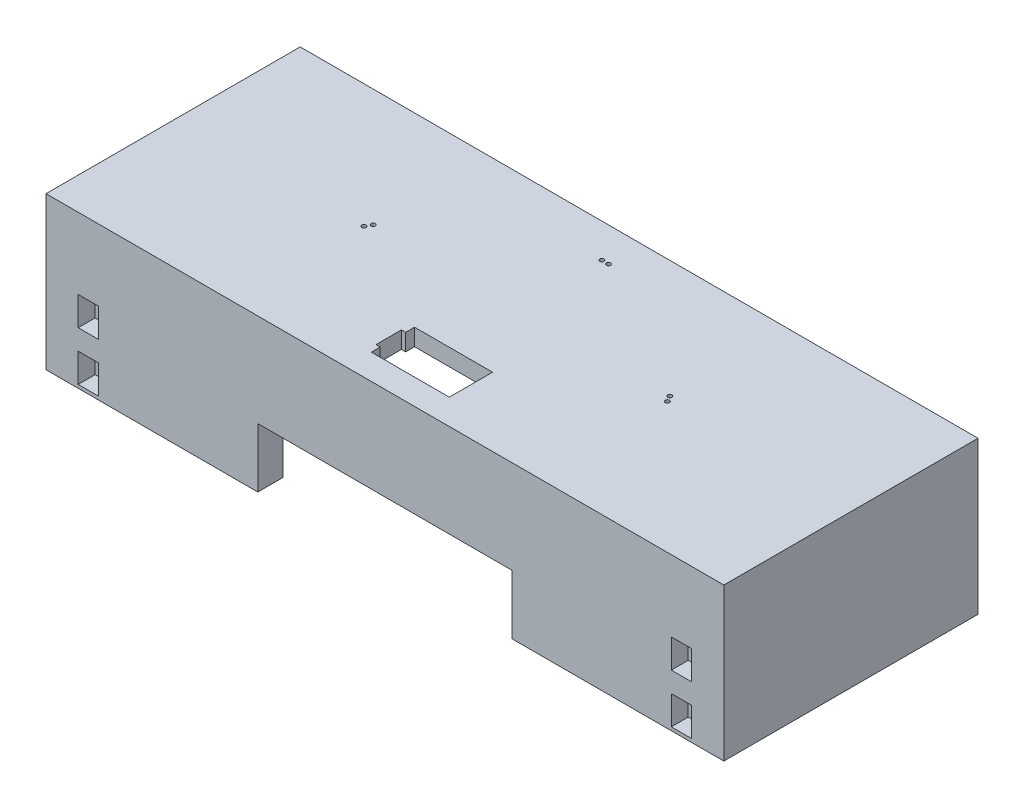
SolidWorks part; units mm, degrees
ref_plane "Front Plane" through (0, 0, 0) normal (0, 0, 1) x (1, 0, 0)
ref_plane "Top Plane" through (0, 0, 0) normal (0, 1, 0) x (1, 0, 0)
ref_plane "Right Plane" through (0, 0, 0) normal (1, 0, 0) x (0, 0, -1)
sketch "Sketch1" plane through (0, 0, 0) normal (0, 1, 0) x (1, 0, 0)
  line L1 (100, 37.5) -> (-100, 37.5)
  line L2 (100, 37.5) -> (100, -37.5)
  line L3 (100, -37.5) -> (-100, -37.5)
  line L4 (-100, 37.5) -> (-100, -37.5)
  line L5 (100, 37.5) -> (-100, -37.5) construction
  line L6 (100, -37.5) -> (-100, 37.5) construction
  point P0 (0, 0)
  dimension "D1" = 200
  dimension "D2" = 75
extrude "Boss-Extrude1" add sketch "Sketch1" along normal mid plane 45
shell "Shell1" thickness 5
sketch "Sketch2" plane through (0, 22.5, 0) normal (0, 1, 0) x (1, 0, 0)
  line L0 (-100, -37.5) -> (100, -37.5) construction
  line L1 (11.5, -30) -> (-11.5, -30)
  line L2 (11.5, -30) -> (11.5, -17.25)
  line L3 (11.5, -17.25) -> (-11.5, -17.25)
  line L4 (-11.5, -30) -> (-11.5, -17.25)
  line L5 (11.5, -30) -> (-11.5, -17.25) construction
  line L6 (11.5, -17.25) -> (-11.5, -30) construction
  point P0 (0, -23.625)
  dimension "D1" = 23
  dimension "D2" = 12.75
  dimension "D3" = 7.5
extrude "Cut-Extrude1" cut sketch "Sketch2" against normal through all
sketch "Sketch3" plane through (0, 22.5, 0) normal (0, 1, 0) x (1, 0, 0)
  line L0 (-11.5, -23.625) -> (11.5, -23.625) construction
  line L1 (-11.5, -17.25) -> (-11.5, -30) construction
  line L2 (11.5, -30) -> (11.5, -17.25) construction
  line L3 (0, -1036.125) -> (0, 48963.875) construction
  line L4 (100, 37.5) -> (-100, 37.5) construction
  line L5 (-44.2755, 1.9375) -> (0, -23.625) construction
  circle A0 centre (0, -23.625) radius 51.125 construction
  point P6 (0, -23.625)
  point P8 (0, 27.5)
  point P14 (-44.2755, 1.9375)
  point P16 (44.2755, 1.9375)
  dimension "D1" = 10
  dimension "D2" = 60
sketch "Sketch4" plane through (0, 0, 32.5) normal (0, 0, -1) x (-1, 0, 0)
  line L4 (-95, -22.5) -> (95, -22.5)
  line L5 (95, -22.5) -> (95, 17.5)
  line L6 (95, 17.5) -> (-95, 17.5)
  line L7 (-95, 17.5) -> (-95, -22.5)
  line L8 (-95, -22.5) -> (95, -22.5)
  line L9 (95, -22.5) -> (95, 17.5)
  line L10 (95, 17.5) -> (-95, 17.5)
  line L11 (-95, 17.5) -> (-95, -22.5)
  dimension "D1" = 0
extrude "Boss-Extrude2" add sketch "Sketch4" along normal blind 2.5
sketch "Sketch5" plane through (0, 0, 37.5) normal (0, 0, 1) x (1, 0, 0)
  line L0 (-90, -6.5) -> (-90, 1) construction
  line L1 (-90, 1) -> (-85, 1) construction
  line L2 (-85, 1) -> (-85, -6.5) construction
  line L3 (-85, -6.5) -> (-90, -6.5) construction
  line L4 (-85, -21) -> (-90, -21) construction
  line L5 (-90, -21) -> (-90, -13.5) construction
  line L6 (-90, -13.5) -> (-85, -13.5) construction
  line L7 (-85, -13.5) -> (-85, -21) construction
  line L8 (90, -13.5) -> (90, -21) construction
  line L9 (90, -21) -> (85, -21) construction
  line L10 (85, -21) -> (85, -13.5) construction
  line L11 (85, -13.5) -> (90, -13.5) construction
  line L12 (90, 1) -> (90, -6.5) construction
  line L13 (90, -6.5) -> (85, -6.5) construction
  line L14 (85, -6.5) -> (85, 1) construction
  line L15 (85, 1) -> (90, 1) construction
  line L16 (-90, -6.5) -> (-90, 1)
  line L17 (-90, 1) -> (-85, 1)
  line L18 (-85, 1) -> (-85, -6.5)
  line L19 (-85, -6.5) -> (-90, -6.5)
  line L20 (-85, -21) -> (-90, -21)
  line L21 (-90, -21) -> (-90, -13.5)
  line L22 (-90, -13.5) -> (-85, -13.5)
  line L23 (-85, -13.5) -> (-85, -21)
  line L24 (90, -13.5) -> (90, -21)
  line L25 (90, -21) -> (85, -21)
  line L26 (85, -21) -> (85, -13.5)
  line L27 (85, -13.5) -> (90, -13.5)
  line L28 (90, 1) -> (90, -6.5)
  line L29 (90, -6.5) -> (85, -6.5)
  line L30 (85, -6.5) -> (85, 1)
  line L31 (85, 1) -> (90, 1)
  line L32 (-84.5, 1.5) -> (-84.5, -7)
  line L33 (-84.5, -7) -> (-90.5, -7)
  line L34 (-90.5, -7) -> (-90.5, 1.5)
  line L35 (-90.5, 1.5) -> (-84.5, 1.5)
  line L36 (-84.5, -13) -> (-84.5, -21.5)
  line L37 (-84.5, -21.5) -> (-90.5, -21.5)
  line L38 (-90.5, -21.5) -> (-90.5, -13)
  line L39 (-90.5, -13) -> (-84.5, -13)
  line L40 (84.5, -21.5) -> (84.5, -13)
  line L41 (84.5, -13) -> (90.5, -13)
  line L42 (90.5, -13) -> (90.5, -21.5)
  line L43 (90.5, -21.5) -> (84.5, -21.5)
  line L44 (84.5, -7) -> (84.5, 1.5)
  line L45 (84.5, 1.5) -> (90.5, 1.5)
  line L46 (90.5, 1.5) -> (90.5, -7)
  line L47 (90.5, -7) -> (84.5, -7)
  dimension "D1" = 0.5
extrude "Cut-Extrude2" cut sketch "Sketch5" against normal blind 5 contours L35 L34 L33 L32 L18 L19 L16 L17 | L19 L18 L17 L16 | L39 L38 L37 L36 L22 L23 L20 L21 | L23 L22 L21 L20 | L47 L46 L45 L44 L30 L31 L28 L29 | L31 L30 L29 L28 | L43 L42 L41 L40 L26 L27 L24 L25 | L27 L26 L25 L24
sketch "Sketch7" plane through (0, 0, -37.5) normal (0, 0, -1) x (-1, 0, 0)
  line L0 (-100, -22.5) -> (100, -22.5) construction
  point P0 (0, -22.5)
hole_wizard "Ø1.0mm Dowel Hole1" positions "Sketch7" profile "Sketch8" hole size "Ø1.0" standard "ANSI Metric"
sketch "Sketch8" plane through (0, -22.5, -37.5) normal (1, 0, 0) x (0, 1, 0)
  line L0 (0, 0) -> (0, 9.5065)
  line L1 (0, 9.5065) -> (7.5, 5)
  line L2 (7.5, 5) -> (7.5, 0)
  line L5 (7.5, 0) -> (0, 0)
  line L10 (0, 9.5065) -> (-7.5, 5) construction
  line L11 (0, -6.35) -> (0, 107.95) construction
  dimension "Hole Dia." = 15
  dimension "Hole Depth" = 5
  dimension "Drill Angle" = 118
sketch "Sketch9" plane through (0, 0, 37.5) normal (0, 0, 1) x (1, 0, 0)
  line L0 (-100, -22.5) -> (100, -22.5) construction
  line L1 (37.5, -22.5) -> (-37.5, -22.5)
  line L2 (37.5, -22.5) -> (37.5, -5)
  line L3 (37.5, -5) -> (-37.5, -5)
  line L4 (-37.5, -22.5) -> (-37.5, -5)
  line L5 (37.5, -22.5) -> (-37.5, -5) construction
  line L6 (37.5, -5) -> (-37.5, -22.5) construction
  point P0 (0, -13.75)
  dimension "D1" = 5
  dimension "D2" = 75
extrude "Cut-Extrude3" cut sketch "Sketch9" against normal up to surface (7.5 mm away) up to face at (0, 8.75, 30)
sketch "Sketch10" plane through (0, 22.5, 0) normal (0, 1, 0) x (1, 0, 0)
  line L0 (-11.5, -17.25) -> (-11.5, -30) construction
  line L1 (-10.25, -19.875) -> (-12.75, -19.875)
  line L2 (-10.25, -19.875) -> (-10.25, -27.375)
  line L3 (-10.25, -27.375) -> (-12.75, -27.375)
  line L4 (-12.75, -19.875) -> (-12.75, -27.375)
  line L5 (-10.25, -19.875) -> (-12.75, -27.375) construction
  line L6 (-10.25, -27.375) -> (-12.75, -19.875) construction
  point P0 (-11.5, -23.625)
  dimension "D1" = 2.5
  dimension "D2" = 7.5
extrude "Cut-Extrude4" cut sketch "Sketch10" against normal up to surface (5 mm away) up to face at (0, 17.5, 11.1875)
sketch "Sketch11" plane through (0, 22.5, 0) normal (0, 1, 0) x (1, 0, 0)
  line L0 (0, -201036.125) -> (0, 248963.875) construction
  line L1 (-44.2755, 1.9375) -> (0, -23.625) construction
  circle A0 centre (0, -23.625) radius 51.125 construction
  point P0 (-1, 27.4902)
  point P1 (1, 27.4902)
  point P7 (-44.7671, 1.0666)
  point P9 (-43.7671, 2.7986)
  point P14 (43.7671, 2.7986)
  point P16 (44.7671, 1.0666)
  dimension "D1" = 1
  dimension "D2" = 1
  dimension "D6" = 1
  dimension "D3" = 1
  dimension "D4" = 1
  dimension "D5" = 1
hole_wizard "Ø1.0mm Dowel Hole2" positions "Sketch11" profile "Sketch12" hole size "Ø1.0" standard "ANSI Metric"
sketch "Sketch12" plane through (-1, 22.5, -27.4902) normal (1, 0, 0) x (0, 0, 1)
  line L0 (0, 0) -> (0, 5.3755)
  line L1 (0, 5.3755) -> (0.625, 5)
  line L2 (0.625, 5) -> (0.625, 0)
  line L5 (0.625, 0) -> (0, 0)
  line L10 (0, 5.3755) -> (-0.625, 5) construction
  line L11 (0, -6.35) -> (0, 107.95) construction
  dimension "Hole Dia." = 1.25
  dimension "Hole Depth" = 5
  dimension "Drill Angle" = 118
